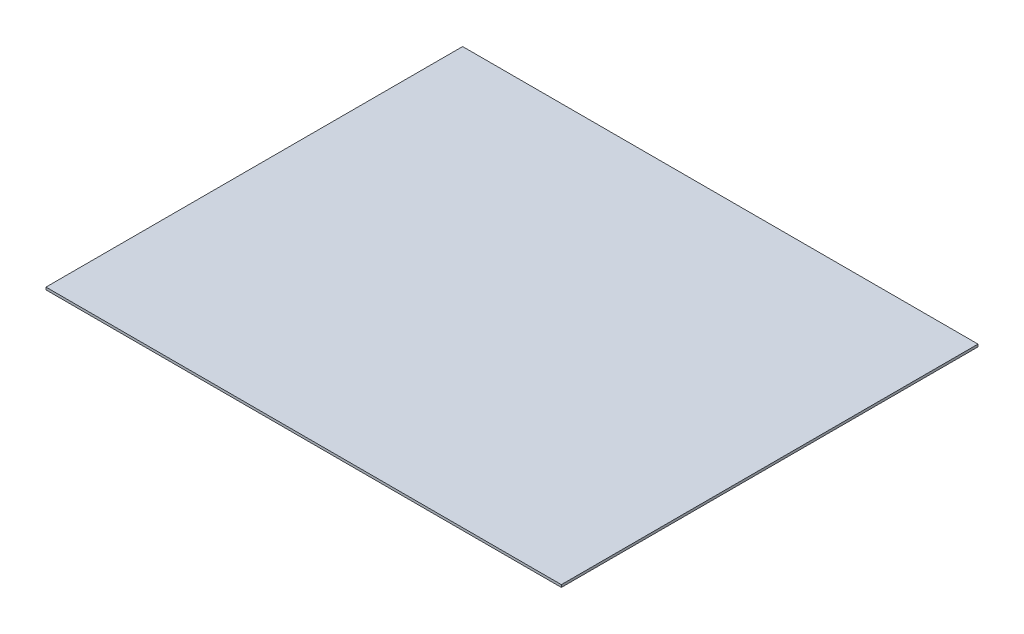
SolidWorks part; units mm, degrees
ref_plane "Front Plane" through (0, 0, 0) normal (0, 0, 1) x (1, 0, 0)
ref_plane "Top Plane" through (0, 0, 0) normal (0, 1, 0) x (1, 0, 0)
ref_plane "Right Plane" through (0, 0, 0) normal (1, 0, 0) x (0, 0, -1)
sketch "Sketch1" plane through (0, 0, 0) normal (0, 1, 0) x (1, 0, 0)
  line L1 (0, 0) -> (261, 0)
  line L2 (0, 0) -> (0, 211)
  line L3 (0, 211) -> (261, 211)
  line L4 (261, 0) -> (261, 211)
  dimension "D1" = 261
  dimension "D2" = 211
extrude "Boss-Extrude1" add sketch "Sketch1" along normal blind 1.25
